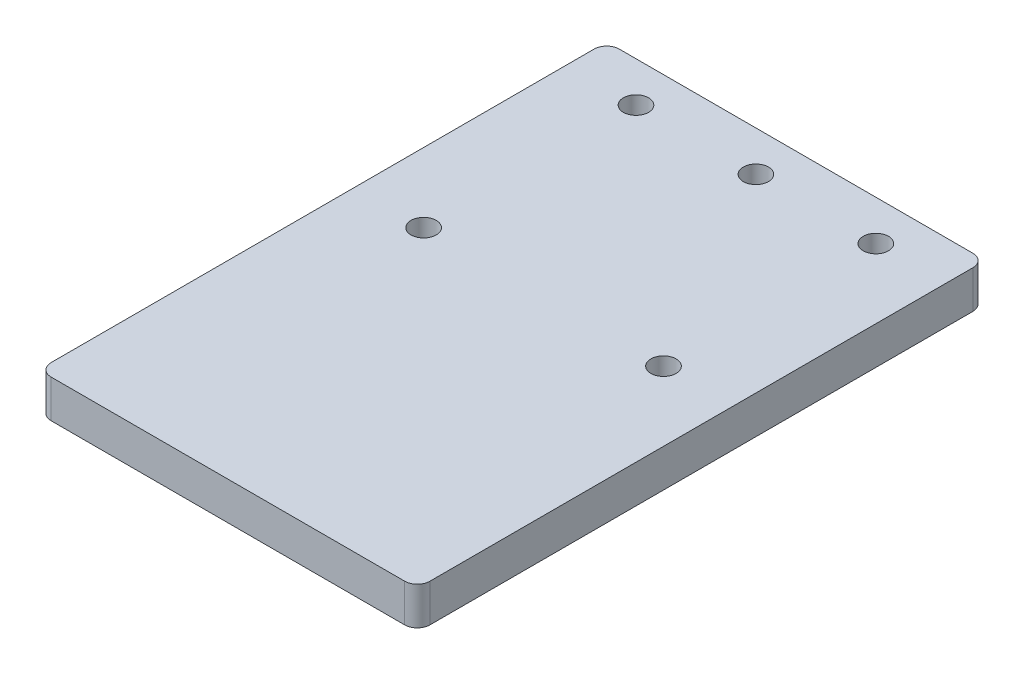
SolidWorks part; units mm, degrees
material "AISI 316 Stainless Steel Sheet (SS)"
ref_plane "Front Plane" through (0, 0, 0) normal (0, 0, 1) x (1, 0, 0)
ref_plane "Top Plane" through (0, 0, 0) normal (0, 1, 0) x (1, 0, 0)
ref_plane "Right Plane" through (0, 0, 0) normal (1, 0, 0) x (0, 0, -1)
sketch "Sketch1" plane through (0, 0, 0) normal (0, 1, 0) x (1, 0, 0)
  line L1 (0, 0) -> (30, 0)
  line L2 (0, 0) -> (0, -45)
  line L3 (0, -45) -> (30, -45)
  line L4 (30, 0) -> (30, -45)
  line L5 (7.5, 0) -> (22.5, 0) construction
  line L6 (7.5, 0) -> (7.5, -25) construction
  line L7 (7.5, -25) -> (22.5, -25) construction
  line L8 (22.5, 0) -> (22.5, -25) construction
  line L9 (10, -12.7) -> (20, -12.7) construction
  line L10 (10, -12.7) -> (10, 0) construction
  line L11 (10, 0) -> (20, 0) construction
  line L12 (20, -12.7) -> (20, 0) construction
  circle A0 centre (15, -3.18) radius 1
  circle A1 centre (5.5, -20) radius 1
  circle A2 centre (24.5, -20) radius 1
  circle A3 centre (24.5, -3.18) radius 1
  circle A4 centre (5.5, -3.18) radius 1
  point P8 (15, 0)
  point P10 (15, -25)
  point P23 (15, -12.7)
  dimension "D2" = 2
  dimension "D8" = 2
  dimension "D1" = 30
  dimension "D3" = 3.18
  dimension "D4" = 45
  dimension "D5" = 3.18
  dimension "D6" = 9.5
  dimension "D9" = 15
  dimension "D10" = 3.18
  dimension "D11" = 25
  dimension "D12" = 10
  dimension "D13" = 20
  dimension "D14" = 12.7
  dimension "D15" = 9.5
extrude "Boss-Extrude1" add sketch "Sketch1" along normal blind 3
fillet "Fillet1" radius 1 4 edges at (0, 1.5, 0) (30, 1.5, 0) (0, 1.5, 45) (30, 1.5, 45)
